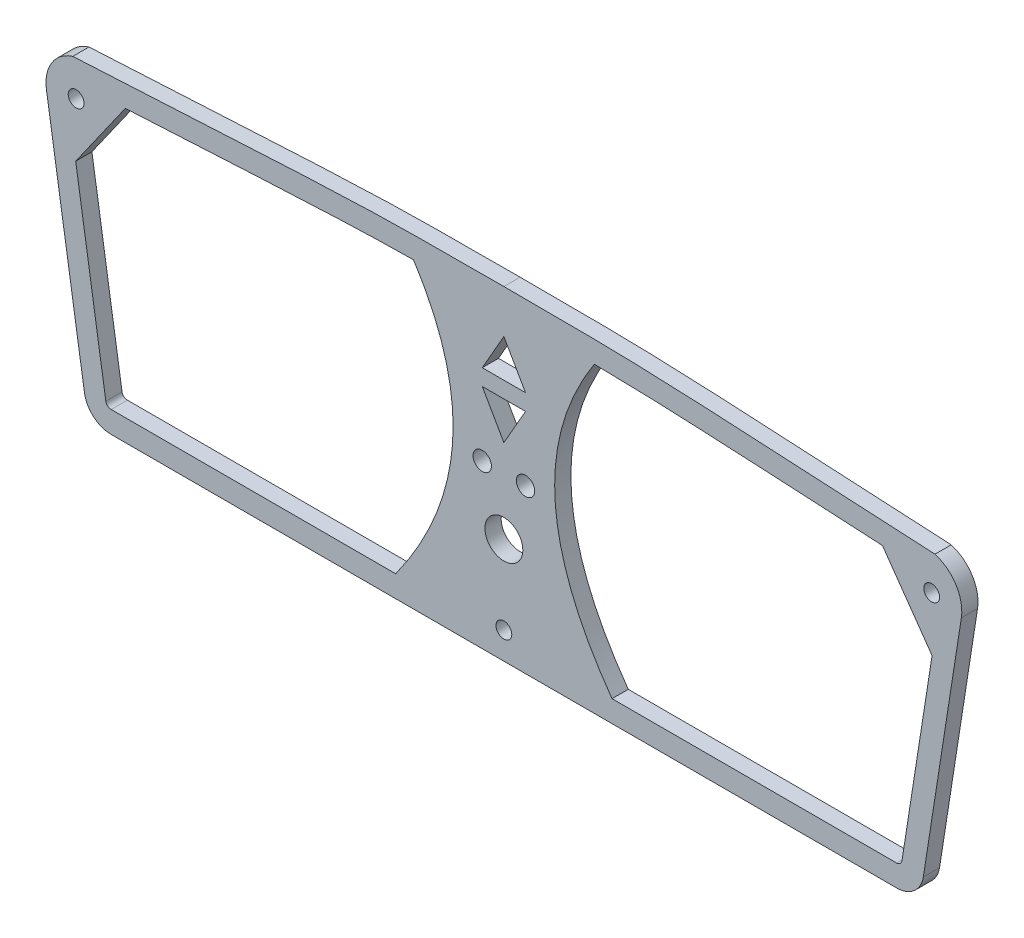
SolidWorks part; units mm, degrees
ref_plane "Alzado" through (0, 0, 0) normal (0, 0, 1) x (1, 0, 0)
ref_plane "Planta" through (0, 0, 0) normal (0, 1, 0) x (1, 0, 0)
ref_plane "Vista lateral" through (0, 0, 0) normal (1, 0, 0) x (0, 0, -1)
sketch "Croquis1" plane through (0, 0, 0) normal (0, 0, 1) x (1, 0, 0)
  line L0 (72.621, -42.7139) -> (-72.621, -42.7139)
  line L1 (79.7182, 14.2861) -> (-79.7182, 14.2861) construction
  line L2 (0, 14.2861) -> (0, 17.2861) construction
  line L3 (-77.7935, 17.2861) -> (77.7935, 17.2861) construction
  line L4 (0, -40.4126) -> (0, 34.1548) construction
  line L5 (-25, 41.2162) -> (-25, -46.3712) construction
  line L6 (-77.5611, -38.4855) -> (-84.5891, 6.5113)
  line L11 (25, 41.2162) -> (25, -46.3712) construction
  line L14 (77.5611, -38.4855) -> (84.5891, 6.5113)
  arc A0 (84.5891, 6.5113) -> (79.7182, 14.2861) centre (77.6729, 7.5915) ccw
  arc A1 (77.5611, -38.4855) -> (72.621, -42.7139) centre (72.621, -37.7139) cw
  arc A2 (-77.5611, -38.4855) -> (-72.621, -42.7139) centre (-72.621, -37.7139) ccw
  arc A3 (-84.5891, 6.5113) -> (-79.7182, 14.2861) centre (-77.6729, 7.5915) cw
  conic Q0 (79.7182, 14.2861) -> (0, 17.2861) control (25, 17.2861) rho 0.75
  conic Q1 (-79.7182, 14.2861) -> (0, 17.2861) control (-25, 17.2861) rho 0.75
  point P15 (-84.627, 12.5288)
  point P27 (0, -42.7139)
  point P28 (0, -42.7139)
  point P40 (0, 9.5288)
  point P61 (0, -42.7139)
  point P62 (84.627, 12.5288)
  dimension "D1" = 5
  dimension "D2" = 7
  dimension "D4" = 60
  dimension "D3" = 3
extrude "Saliente-Extruir3" add sketch "Croquis1" along normal blind 3 contours Q0 Q1 A3 L6 A2 L0 A1 L14 A0
sketch "Croquis10" plane through (0, 0, 0) normal (0, 0, -1) x (-1, 0, 0)
  line L0 (-79.1761, -2.225) -> (-70, 10.8116)
  line L1 (79.1761, -2.225) -> (70, 10.8116)
  line L2 (-20, 27.3642) -> (-20, -66.0706) construction
  line L3 (-89.1533, -2.1273) -> (92.9339, -3.91) construction
  line L4 (-70, 32.4884) -> (-70, -57.6963) construction
  line L5 (70, -55.635) -> (70, -62.635) construction
  line L6 (-80.637, 7.1286) -> (-73.609, -37.8682)
  line L7 (-72.621, -38.7139) -> (72.621, -38.7139)
  line L8 (73.609, -37.8682) -> (80.637, 7.1286)
  line L9 (-79.1761, -2.225) -> (-73.609, -37.8682)
  line L10 (-20, -38.7139) -> (-72.621, -38.7139)
  line L11 (73.609, -37.8682) -> (79.1761, -2.225)
  line L12 (0, -66.0706) -> (0, 45.5866) construction
  line L13 (20, 32.4884) -> (20, -73.2967) construction
  line L14 (10, 34.6369) -> (10, -62.635) construction
  line L15 (17, 23.9593) -> (17, 3.2579) construction
  line L16 (72.621, -38.7139) -> (20, -38.7139)
  arc A8 (-78.9106, 10.3243) -> (-80.637, 7.1286) centre (-77.6729, 7.5915) ccw
  arc A9 (-73.609, -37.8682) -> (-72.621, -38.7139) centre (-72.621, -37.7139) ccw
  arc A10 (72.621, -38.7139) -> (73.609, -37.8682) centre (72.621, -37.7139) ccw
  arc A11 (80.637, 7.1286) -> (78.9106, 10.3243) centre (77.6729, 7.5915) ccw
  arc A13 (-73.609, -37.8682) -> (-72.621, -38.7139) centre (-72.621, -37.7139) ccw
  arc A14 (72.621, -38.7139) -> (73.609, -37.8682) centre (72.621, -37.7139) ccw
  spline S1 degree 2 poles (20, -38.7139) (0.4038, -11.4379) (17, 13.6086) knots 0 0 0 1 1 1
  spline S2 degree 2 poles (-20, -38.7139) (-0.4038, -11.4379) (-17, 13.6086) knots 0 0 0 1 1 1
  spline S4 degree 3 poles (2127.4277, 3107.9879) (1321.8072, -103.3293) (691.7435, -22.6635) (52.6222, 11.7513) (46.0499, 12.1034) (36.1891, 12.5892) (32.9019, 12.7438) (26.3256, 13.0031) (23.0364, 13.1028) (16.455, 13.2247) (13.1641, 13.2517) (-251.0773, 14.4861) (-512.4874, -58.3996) (-748.9997, 3882.2691) knots -23.81136 -23.81136 -23.81136 -23.81136 0.25 0.25 0.5 0.5 0.625 0.625 0.75 0.75 0.875 0.875 10.786587 10.786587 10.786587 10.786587 only from (78.9106, 10.3243) to (0, 13.2861)
  spline S5 degree 3 poles (749.0785, 3882.2918) (512.4869, -58.3999) (251.0778, 14.4861) (-13.1641, 13.2517) (-16.455, 13.2247) (-23.0364, 13.1028) (-26.3256, 13.0031) (-32.9019, 12.7438) (-36.1891, 12.5892) (-46.0499, 12.1034) (-52.6222, 11.7513) (-691.748, -22.6638) (-1321.8163, -103.3304) (-2127.4302, 3108.0565) knots -9.786601 -9.786601 -9.786601 -9.786601 0.125 0.125 0.25 0.25 0.375 0.375 0.5 0.5 0.75 0.75 24.81153 24.81153 24.81153 24.81153 only from (0, 13.2861) to (-78.9106, 10.3243)
  spline S6 degree 3 poles (70, 10.8116) (66.3982, 11.008) (62.7964, 11.2034) (52.6222, 11.7513) (46.0499, 12.1034) (36.1891, 12.5892) (32.9019, 12.7438) (26.3256, 13.0031) (23.0364, 13.1028) (18.7434, 13.1823) (17.741, 13.1977) (16.7387, 13.2106) knots 0.112988 0.112988 0.112988 0.112988 0.25 0.25 0.5 0.5 0.625 0.625 0.75 0.75 0.788074 0.788074 0.788074 0.788074
  spline S7 degree 3 poles (-16.7387, 13.2106) (-17.741, 13.1977) (-18.7434, 13.1823) (-23.0364, 13.1028) (-26.3256, 13.0031) (-32.9019, 12.7438) (-36.1891, 12.5892) (-46.0499, 12.1034) (-52.6222, 11.7513) (-62.7964, 11.2034) (-66.3982, 11.008) (-70, 10.8116) knots 0.211926 0.211926 0.211926 0.211926 0.25 0.25 0.375 0.375 0.5 0.5 0.75 0.75 0.887012 0.887012 0.887012 0.887012
  point P8 (-79.1761, -2.225)
  point P9 (-70, 10.8116)
  point P32 (20, 13.159)
  point P33 (20, -38.7139)
  point P38 (10, -3.098)
  dimension "D2" = 70
  dimension "D3" = 70
  dimension "D4" = 3
  dimension "D5" = 20
  dimension "D6" = 20
  dimension "D7" = 10
  dimension "D8" = 17
  dimension "D1" = 4
extrude "Cortar-Extruir2" cut sketch "Croquis10" against normal blind 3 contours L1 S6 S1 L16 A14 L11 | S2 S7 L0 L9 A13 L10
sketch "Croquis11" plane through (0, 0, 3) normal (0, 0, 1) x (1, 0, 0)
  line L0 (-74.588, 4.2933) -> (-83.6049, 11.3079) construction
  line L1 (-79.1761, -2.225) -> (-70, 10.8116) construction
  line L2 (74.588, 4.2933) -> (83.6049, 11.3079) construction
  line L3 (79.1761, -2.225) -> (70, 10.8116) construction
  line L4 (-10.8705, -37.7139) -> (8.775, -37.7139) construction
  line L5 (0, 0) -> (0, -68.1141) construction
  line L6 (72.621, -42.7139) -> (-72.621, -42.7139) construction
  line L7 (-7.9356, -12.6387) -> (7.8138, -12.6387) construction
  line L8 (-4, -8.005) -> (-4, -16.8566) construction
  line L9 (4, -8.005) -> (4, -16.8566) construction
  arc A0 (-79.7182, 14.2861) -> (-84.5891, 6.5113) centre (-77.6729, 7.5915) ccw construction
  arc A1 (84.5891, 6.5113) -> (79.7182, 14.2861) centre (77.6729, 7.5915) ccw construction
  circle A2 centre (0, -23.1736) radius 3.5
  point P14 (79.0965, 7.8006)
  point P15 (-79.0965, 7.8006)
  point P29 (-4, -12.6387)
  point P31 (4, -12.6387)
  dimension "D1" = 5
  dimension "D2" = 4
  dimension "D3" = 4
hole_wizard "Taladro de margen para #31" positions "Croquis3D3" profile "Croquis13" hole size "#3" standard "Ansi Inch" end condition through all
sketch3d "Croquis3D3"
  line L0 (-10.8705, -37.7139, 3) -> (8.775, -37.7139, 3) construction
  line L1 (0, 0, 3) -> (0, -68.1141, 3) construction
  point P0 (79.0965, 7.8006, 3)
  point P3 (-79.0965, 7.8006, 3)
  point P6 (0, -37.7139, 3)
sketch "Croquis13" plane through (79.0965, 7.8006, 3) normal (1, 0, 0) x (0, -1, 0)
  line L0 (0, 0) -> (0, 3)
  line L1 (0, 3) -> (1.4605, 3)
  line L2 (1.4605, 3) -> (1.4605, 0)
  line L5 (1.4605, 0) -> (0, 0)
  line L11 (0, -6.35) -> (0, 107.95) construction
  dimension "Diámetro de taladro hasta el siguiente" = 2.921
  dimension "Profundidad de taladro hasta el siguiente" = 3
sketch "Croquis14" plane through (0, 0, 3) normal (0, 0, 1) x (1, 0, 0)
  line L0 (0, 35.4133) -> (0, -21.9384) construction
  line L1 (8.5, 12.2861) -> (8.5, -13.7139) construction
  line L2 (8.5, -13.7139) -> (-8.5, -13.7139) construction
  line L3 (-8.5, -13.7139) -> (-8.5, 12.2861) construction
  line L4 (0, 0) -> (0, -68.1141) construction
  line L5 (-8.5, 12.2861) -> (8.5, 12.2861) construction
  line L6 (0, 17.2861) -> (0, 18.2476)
  line L7 (-8.5, 9.2861) -> (8.5, 9.2861) construction
  line L8 (-10.5, 2.2861) -> (8.5, 2.2861) construction
  line L9 (-8.5, -0.7139) -> (8.5, -0.7139) construction
  line L10 (-8.5, -7.7139) -> (8.5, -7.7139) construction
  line L11 (-4, 22.6737) -> (-4, -19.9721) construction
  line L12 (4, 22.6737) -> (4, -21.2096) construction
  line L13 (-4, -0.7139) -> (0, -7.7139)
  line L14 (0, -7.7139) -> (4, -0.7139)
  line L15 (4, -0.7139) -> (-4, -0.7139)
  line L16 (-4, 2.2861) -> (0, 9.2861)
  line L17 (0, 9.2861) -> (4, 2.2861)
  line L18 (4, 2.2861) -> (-4, 2.2861)
  line L19 (-4, 2.2861) -> (-4.101, 2.328)
  point P23 (-4, -0.7139)
  point P24 (-4, 2.2861)
  point P25 (4, 2.2861)
  point P26 (4, -0.7139)
  point P27 (0, -7.7139)
  point P28 (0, 9.2861)
  dimension "D1" = 4
  dimension "D2" = 17
  dimension "D3" = 5
  dimension "D4" = 17
  dimension "D5" = 4
  dimension "D6" = 26
  dimension "D7" = 3
  dimension "D8" = 7
  dimension "D9" = 7
extrude "Cortar-Extruir3" cut sketch "Croquis14" against normal blind 3 contours L18 L17 L16 | L14 L15 L13
hole_wizard "Taladro de margen para M31" positions "Croquis3D4" profile "Croquis15" hole size "M3" standard "AS" end condition through all
sketch3d "Croquis3D4"
  point P0 (-4, -12.6387, 3)
  point P3 (4, -12.6387, 3)
sketch "Croquis15" plane through (-4, -12.6387, 3) normal (1, 0, 0) x (0, -1, 0)
  line L0 (0, 0) -> (0, 3)
  line L1 (0, 3) -> (1.7, 3)
  line L2 (1.7, 3) -> (1.7, 0)
  line L5 (1.7, 0) -> (0, 0)
  line L11 (0, -6.35) -> (0, 107.95) construction
  dimension "Diámetro de taladro hasta el siguiente" = 3.4
  dimension "Profundidad de taladro hasta el siguiente" = 3
extrude "Cortar-Extruir4" cut sketch "Croquis11" against normal blind 4
sketch "Croquis16" plane through (0, 0, 3) normal (0, 0, 1) x (1, 0, 0)
  line L0 (-2.3, -12.6387) -> (2.3, -12.6387) construction
  line L1 (0, -23.1736) -> (0, -19.6736)
  line L2 (0, -23.1736) -> (5.2148, -17.9589)
  line L3 (0, -23.1736) -> (-5.3243, -17.8494)
  line L4 (0, -23.1736) -> (-5.108, -28.2817)
  line L5 (0, -23.1736) -> (5.7098, -28.8834)
  line L6 (0, -23.1736) -> (0, -26.6736)
  line L7 (-4, -8.8182) -> (-4, -16.7741)
  line L8 (4, 17.2259) -> (4, -16.7741)
  line L9 (-7.4883, -16.127) -> (-0.5117, -9.1504)
  line L10 (-0.4223, -16.2165) -> (-7.5777, -9.061)
  line L11 (7.5023, -16.141) -> (0.4977, -9.1364)
  line L12 (0.8141, -15.8246) -> (7.1859, -9.4528)
  circle A1 centre (-4, -12.6387) radius 1.7 construction
  circle A2 centre (4, -12.6387) radius 1.7 construction
  circle A3 centre (4, -12.6387) radius 2.25
  circle A4 centre (-4, -12.6387) radius 2.25
  circle A5 centre (0, -23.1736) radius 3.5 construction
  circle A9 centre (-4, -12.6387) radius 3.5
  circle A10 centre (4, -12.6387) radius 3.5
  text T0 "<b>ON</b>" font "BankGothic Md BT" height in points 10
  text T1 "<b>OFF</b>" font "BankGothic Md BT" height in points 10
  text T2 "<b>Charger</b>" font "BankGothic Md BT" height in points 5
  text T3 "STATE" font "BankGothic Md BT" height in points 5
  point P27 (-5.591, -11.0477)
  point P30 (-4, -12.6387)
  point P36 (-4, -12.6387)
  point P39 (4, -12.6387)
  point P42 (4, -12.6387)
  point P43 (-6.4749, -10.1638)
  point P44 (-1.5251, -10.1638)
  point P45 (-2.409, -11.0477)
  point P46 (1.5251, -10.1638)
  point P47 (-6.4749, -15.1136)
  point P48 (-1.5251, -15.1136)
  point P49 (2.409, -11.0477)
  point P50 (5.591, -11.0477)
  dimension "D1" = 45
  dimension "D5" = 45
  dimension "D2" = 45
  dimension "D3" = 90
  dimension "D4" = 45
  dimension "D6" = 45
  dimension "D7" = 45
  dimension "D8" = 45
